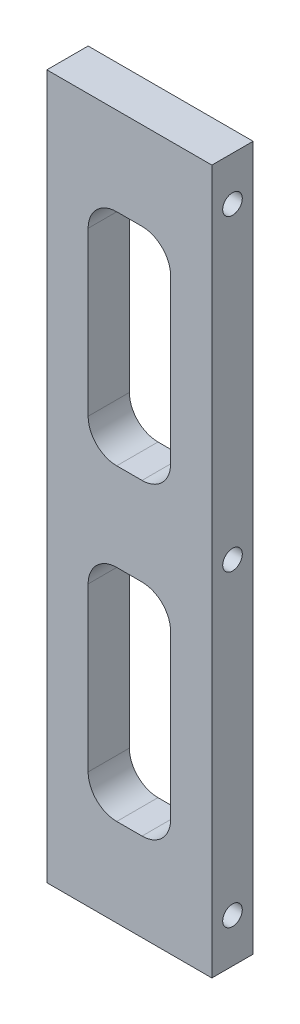
SolidWorks part; units mm, degrees
material "6061-T6 (SS)"
ref_plane "Front Plane" through (0, 0, 0) normal (0, 0, 1) x (1, 0, 0)
ref_plane "Top Plane" through (0, 0, 0) normal (0, 1, 0) x (1, 0, 0)
ref_plane "Right Plane" through (0, 0, 0) normal (1, 0, 0) x (0, 0, -1)
sketch "Sketch1" plane through (0, 0, 0) normal (0, 0, 1) x (1, 0, 0)
  line L1 (-9.525, -40.64) -> (9.525, -40.64)
  line L2 (-9.525, -40.64) -> (-9.525, 40.64)
  line L3 (-9.525, 40.64) -> (9.525, 40.64)
  line L4 (9.525, -40.64) -> (9.525, 40.64)
  line L5 (-9.525, -40.64) -> (9.525, 40.64) construction
  line L6 (-9.525, 40.64) -> (9.525, -40.64) construction
  point P0 (0, 0)
  dimension "D1" = 19.05
  dimension "D2" = 81.28
extrude "Boss-Extrude1" add sketch "Sketch1" along normal blind 4.7625
sketch "Sketch2" plane through (0, 0, 4.7625) normal (0, 0, 1) x (1, 0, 0)
  line L0 (-9.525, 0) -> (9.525, 0) construction
  line L1 (-9.525, 40.64) -> (-9.525, -40.64) construction
  line L2 (9.525, -40.64) -> (9.525, 40.64) construction
  line L3 (0, 40.64) -> (0, 0) construction
  line L4 (9.525, 40.64) -> (-9.525, 40.64) construction
  line L5 (-4.7625, -30.48) -> (4.7625, -5.08) construction
  line L6 (-4.7625, 5.08) -> (4.7625, 5.08)
  line L7 (-4.7625, 5.08) -> (-4.7625, 30.48)
  line L8 (-4.7625, 30.48) -> (4.7625, 30.48)
  line L9 (4.7625, 5.08) -> (4.7625, 30.48)
  line L10 (-4.7625, 5.08) -> (4.7625, 30.48) construction
  line L11 (-4.7625, 30.48) -> (4.7625, 5.08) construction
  line L12 (-4.7625, -5.08) -> (4.7625, -30.48) construction
  line L13 (4.7625, -5.08) -> (4.7625, -30.48)
  line L14 (-4.7625, -30.48) -> (4.7625, -30.48)
  line L15 (-4.7625, -5.08) -> (-4.7625, -30.48)
  line L16 (-4.7625, -5.08) -> (4.7625, -5.08)
  point P11 (0, 17.78)
  point P20 (0, -17.78)
  dimension "D1" = 4.7625
  dimension "D2" = 5.08
  dimension "D3" = 10.16
extrude "Cut-Extrude1" cut sketch "Sketch2" against normal through all
fillet "Fillet1" radius 3.302 8 edges at (-4.7625, -30.48, 2.3813) (4.7625, -30.48, 2.3813) (-4.7625, -5.08, 2.3813) (4.7625, -5.08, 2.3813) (-4.7625, 5.08, 2.3813) (4.7625, 5.08, 2.3813) (4.7625, 30.48, 2.3813) (-4.7625, 30.48, 2.3813)
hole_wizard "#4-40 Tapped Hole1" positions "Sketch4" profile "Sketch5" tap size "#4-40" standard "ANSI Inch" end condition through all
sketch "Sketch4" plane through (9.525, 0, 0) normal (1, 0, 0) x (0, 0, -1)
  line L0 (-2.3813, 40.64) -> (-2.3813, -40.64) construction
  line L1 (-4.7625, 40.64) -> (0, 40.64) construction
  line L2 (-4.7625, -40.64) -> (0, -40.64) construction
  line L3 (-4.7625, 40.64) -> (0, 40.64) construction
  point P9 (-2.3812, 35.56)
  point P11 (-2.3813, 0)
  point P13 (-2.3812, -35.56)
  dimension "D1" = 5.08
  dimension "D2" = 5.08
sketch "Sketch5" plane through (9.525, 35.56, 2.3812) normal (0, 1, 0) x (0, 0, -1)
  line L0 (0, 0) -> (0, 19.05)
  line L1 (0, 19.05) -> (1.1303, 19.05)
  line L2 (1.1303, 19.05) -> (1.1303, 0)
  line L5 (1.1303, 0) -> (0, 0)
  line L11 (0, -6.35) -> (0, 107.95) construction
  dimension "Thru Tap Drill Dia." = 2.2606
  dimension "Thru Tap Drill Depth" = 19.05
cosmetic thread "Hole Thread1" parameters "D2"=2.8448
cosmetic thread "Hole Thread2" parameters "D2"=2.8448
cosmetic thread "Hole Thread3" parameters "D2"=2.8448
